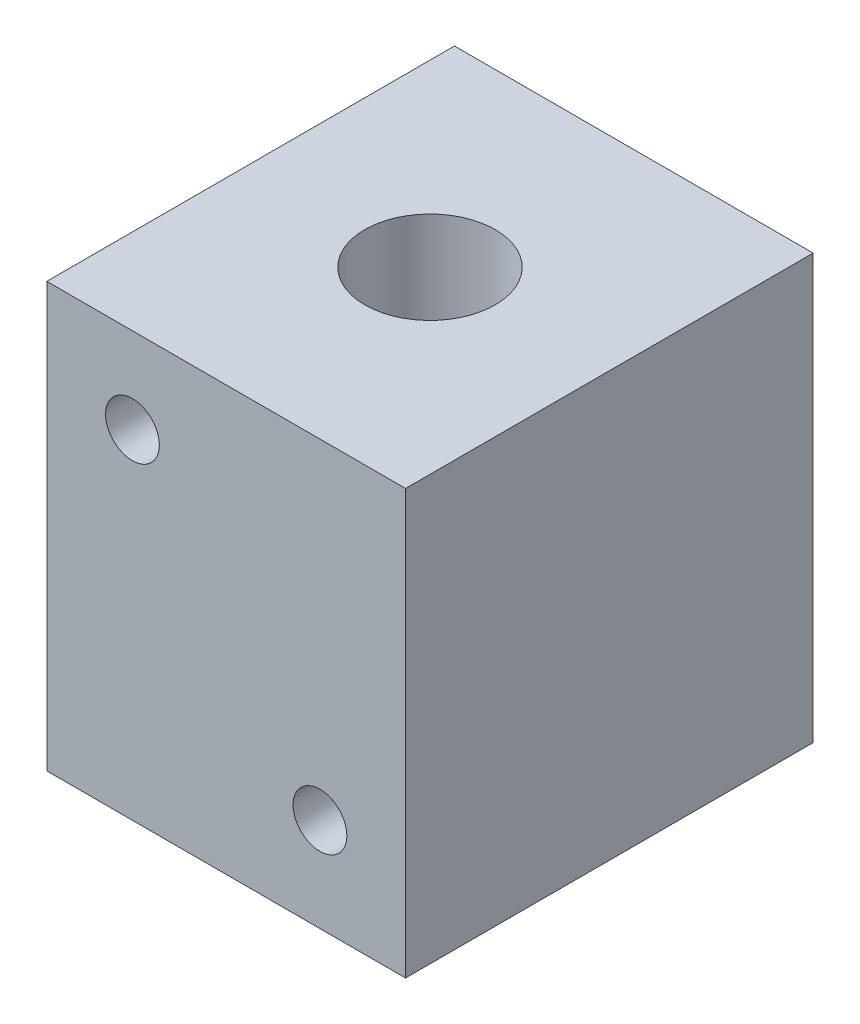
SolidWorks part; units mm, degrees
ref_plane "Front Plane" through (0, 0, 0) normal (0, 0, 1) x (1, 0, 0)
ref_plane "Top Plane" through (0, 0, 0) normal (0, 1, 0) x (1, 0, 0)
ref_plane "Right Plane" through (0, 0, 0) normal (1, 0, 0) x (0, 0, -1)
sketch "Sketch1" plane through (0, 0, 0) normal (0, 1, 0) x (1, 0, 0)
  line L1 (-11, -12.5) -> (11, -12.5)
  line L2 (-11, -12.5) -> (-11, 12.5)
  line L3 (-11, 12.5) -> (11, 12.5)
  line L4 (11, -12.5) -> (11, 12.5)
  line L5 (-11, -12.5) -> (11, 12.5) construction
  line L6 (-11, 12.5) -> (11, -12.5) construction
  point P0 (0, 0)
  dimension "D1" = 25
  dimension "D2" = 22
extrude "Boss-Extrude1" add sketch "Sketch1" along normal blind 26
sketch "Sketch2" plane through (0, 26, 0) normal (0, 1, 0) x (1, 0, 0)
  circle A0 centre (0, 0) radius 4
  dimension "D1" = 8
extrude "Cut-Extrude2" cut sketch "Sketch2" against normal blind 17
sketch "Sketch3" plane through (0, 0, 12.5) normal (0, 0, 1) x (1, 0, 0)
  line L0 (-11, 26) -> (-11, 0) construction
  line L1 (11, 26) -> (11, 0) construction
  line L2 (-11, 26) -> (11, 26) construction
  circle A0 centre (-5.75, 20.75) radius 1.65
  circle A1 centre (5.75, 5.75) radius 1.65
  point P10 (-5.5663, 22.5053)
  dimension "D5" = 3.3
  dimension "D1" = 5.25
  dimension "D2" = 5.25
  dimension "D3" = 15
  dimension "D4" = 5.25
extrude "Cut-Extrude3" cut sketch "Sketch3" against normal blind 10
